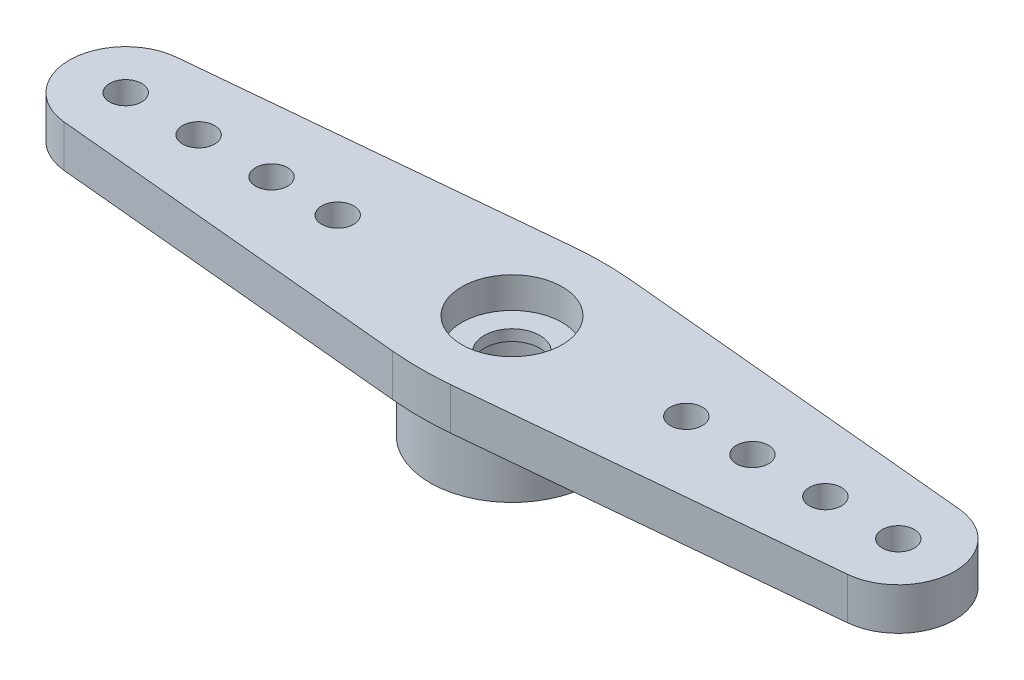
SolidWorks part; units mm, degrees
ref_plane "Front Plane" through (0, 0, 0) normal (0, 0, 1) x (1, 0, 0)
ref_plane "Top Plane" through (0, 0, 0) normal (0, 1, 0) x (1, 0, 0)
ref_plane "Right Plane" through (0, 0, 0) normal (1, 0, 0) x (0, 0, -1)
sketch "Sketch1" plane through (0, 0, 0) normal (0, 1, 0) x (1, 0, 0)
  circle A0 centre (0, 0) radius 3.3655
  circle A1 centre (0, 0) radius 2.2352
  dimension "D1" = 6.731
  dimension "D2" = 4.4704
extrude "Boss-Extrude1" add sketch "Sketch1" along normal blind 2.54
sketch "Sketch2" plane through (0, 2.54, 0) normal (0, 1, 0) x (1, 0, 0)
  line L0 (0, 0) -> (50000, 0) construction
  line L1 (0, 0) -> (0, 50000) construction
  line L2 (0, 3.8227) -> (16.0923, 2.3075)
  line L3 (0, -3.8227) -> (16.0923, -2.3075)
  line L4 (0, -3.8227) -> (-16.0923, -2.3075)
  line L5 (0, 3.8227) -> (-16.0923, 2.3075)
  circle A0 centre (15.875, 0) radius 0.6604
  circle A1 centre (12.8778, 0) radius 0.6604
  circle A2 centre (9.8806, 0) radius 0.6604
  circle A3 centre (7.1628, 0) radius 0.6604
  circle A4 centre (15.875, 0) radius 2.3178
  circle A5 centre (0, 0) radius 3.8227
  circle A6 centre (-15.875, 0) radius 2.3178
  circle A7 centre (-7.1628, 0) radius 0.6604
  circle A8 centre (-9.8806, 0) radius 0.6604
  circle A9 centre (-12.8778, 0) radius 0.6604
  circle A10 centre (-15.875, 0) radius 0.6604
  circle A11 centre (0, 0) radius 1.143
  circle M1 centre (0, 0) radius 3.3655
  circle M2 centre (0, 0) radius 2.2352
  dimension "D1" = 1.3208
  dimension "D6" = 4.6355
  dimension "D7" = 7.6454
  dimension "D8" = 2.286
  dimension "D2" = 15.875
  dimension "D3" = 2.9972
  dimension "D4" = 5.9944
  dimension "D5" = 8.7122
extrude "Boss-Extrude2" add sketch "Sketch2" along normal blind 1.7272 contours L5 A6 L4 A5 A8 A7 A9 | A6 A10 | A5 L3 A4 L2 A1 A2 A3 | A4 A0 | M1 M2 | L3 A5 L2 L5 L4 M1 | A11 M2
fillet "Fillet1" radius 12.7 2 edges at (0, 3.4036, -3.8227) (0, 3.4036, 3.8227)
sketch "Sketch3" plane through (0, 4.2672, 0) normal (0, 1, 0) x (1, 0, 0)
  circle A0 centre (0, 0) radius 2.0638
  circle M17 centre (0, 0) radius 1.143
  dimension "D1" = 4.1275
extrude "Cut-Extrude1" cut sketch "Sketch3" against normal blind 1.27 contours A0 M17
scale "Scale1" bodies to scale 103 scale about centroid uniform scaling yes scale factor 1.483924
